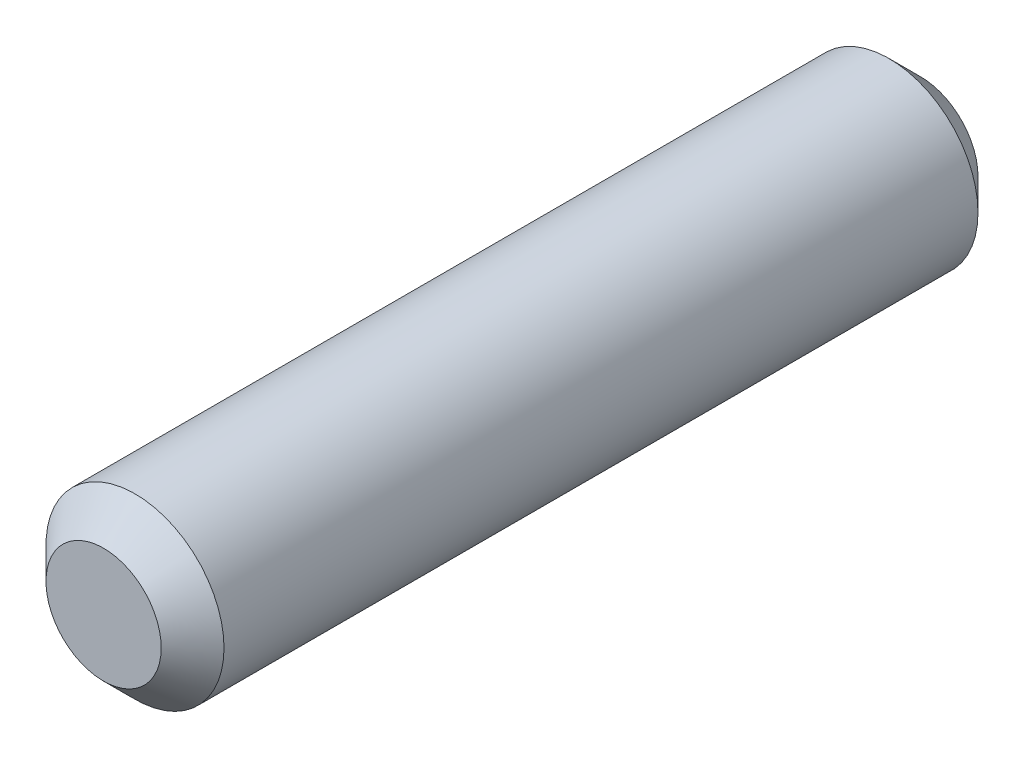
SolidWorks part; units mm, degrees
material "Brass"
ref_plane "Front Plane" through (0, 0, 0) normal (0, 0, 1) x (1, 0, 0)
ref_plane "Top Plane" through (0, 0, 0) normal (0, 1, 0) x (1, 0, 0)
ref_plane "Right Plane" through (0, 0, 0) normal (1, 0, 0) x (0, 0, -1)
sketch "Sketch1" plane through (0, 0, 0) normal (0, 0, 1) x (1, 0, 0)
  circle A0 centre (0, 0) radius 8.5
  dimension "D1" = 17
extrude "Boss-Extrude1" add sketch "Sketch1" along normal mid plane 78
chamfer "Chamfer1" distance 3 angle 45 2 edges at (8.5, 0, -39) (8.5, 0, 39)
